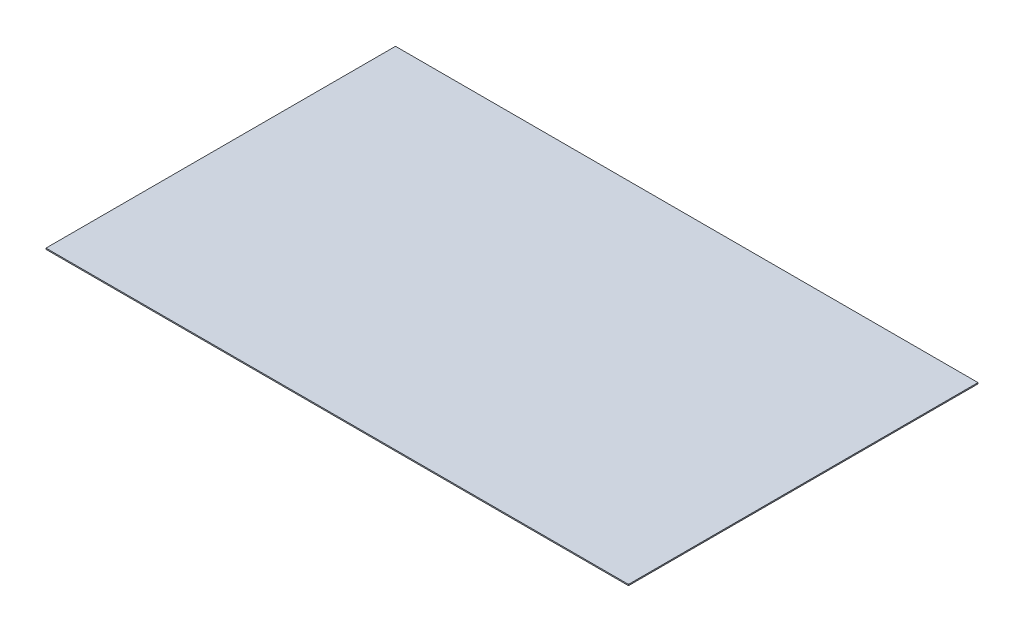
SolidWorks part; units mm, degrees
material "Balsa"
ref_plane "Front Plane" through (0, 0, 0) normal (0, 0, 1) x (1, 0, 0)
ref_plane "Top Plane" through (0, 0, 0) normal (0, 1, 0) x (1, 0, 0)
ref_plane "Right Plane" through (0, 0, 0) normal (1, 0, 0) x (0, 0, -1)
sketch "Sketch1" plane through (0, 0, 0) normal (0, 1, 0) x (1, 0, 0)
  line L1 (-68.9594, 35.291) -> (4931.0406, 35.291)
  line L2 (-68.9594, 35.291) -> (-68.9594, -2964.709)
  line L3 (-68.9594, -2964.709) -> (4931.0406, -2964.709)
  line L4 (4931.0406, 35.291) -> (4931.0406, -2964.709)
  dimension "D1" = 5000
  dimension "D2" = 3000
extrude "Boss-Extrude1" add sketch "Sketch1" along normal blind 10
